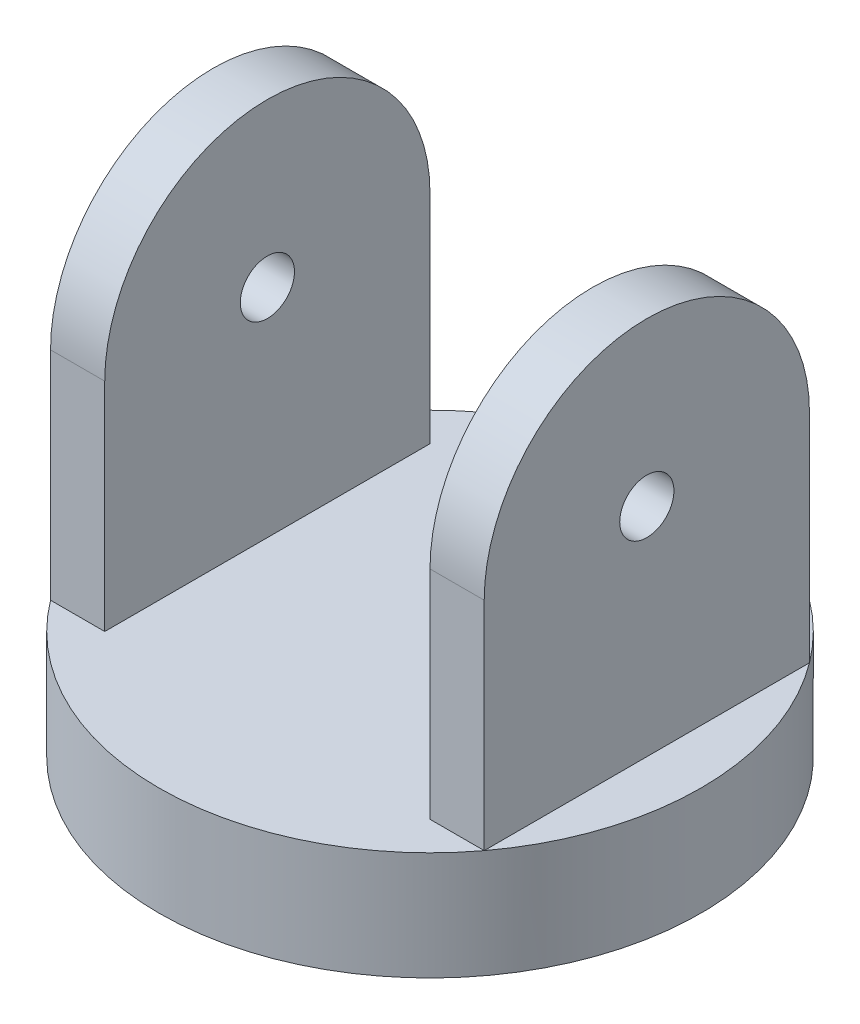
SolidWorks part; units mm, degrees
material "1060 Alloy"
ref_plane "Front Plane" through (0, 0, 0) normal (0, 0, 1) x (1, 0, 0)
ref_plane "Top Plane" through (0, 0, 0) normal (0, 1, 0) x (1, 0, 0)
ref_plane "Right Plane" through (0, 0, 0) normal (1, 0, 0) x (0, 0, -1)
sketch "Sketch1" plane through (0, 0, 0) normal (0, 1, 0) x (1, 0, 0)
  circle A0 centre (0, 0) radius 25
extrude "Boss-Extrude1" add sketch "Sketch1" along normal blind 10
sketch "Sketch2" plane through (0, 10, 0) normal (0, 1, 0) x (1, 0, 0)
  line L0 (20, -15) -> (15, -15)
  line L1 (20, -15) -> (20, 15)
  line L2 (15, -15) -> (15, 15)
  line L3 (-15, 15) -> (-20, 15)
  line L4 (-15, -15) -> (-20, -15)
  line L5 (-15, -15) -> (-15, 15)
  line L6 (-20, -15) -> (-20, 15)
  line L8 (20, 15) -> (15, 15)
  circle A1 centre (0, 0) radius 25 construction
  dimension "D1" = 30
  dimension "D2" = 40
  dimension "D3" = 15
extrude "Boss-Extrude2" add sketch "Sketch2" along normal blind 40
sketch "Sketch3" plane through (-20, 0, 0) normal (-1, 0, 0) x (0, 0, 1)
  line L0 (-15, 50) -> (-15, 10) construction
  line L1 (15, 50) -> (15, 10) construction
  line L2 (-15, 30) -> (-15, 50)
  line L4 (15, 50) -> (15, 30)
  arc A0 (15, 30) -> (-15, 30) centre (0, 30) ccw
  circle A1 centre (0, 30) radius 2.5
  line M2 (15, 10) -> (15, 50)
  line M3 (15, 50) -> (-15, 50)
  line M4 (-15, 50) -> (-15, 10)
extrude "Cut-Extrude1" cut sketch "Sketch3" against normal through all contours A0 M2 M3 M4 | A1
